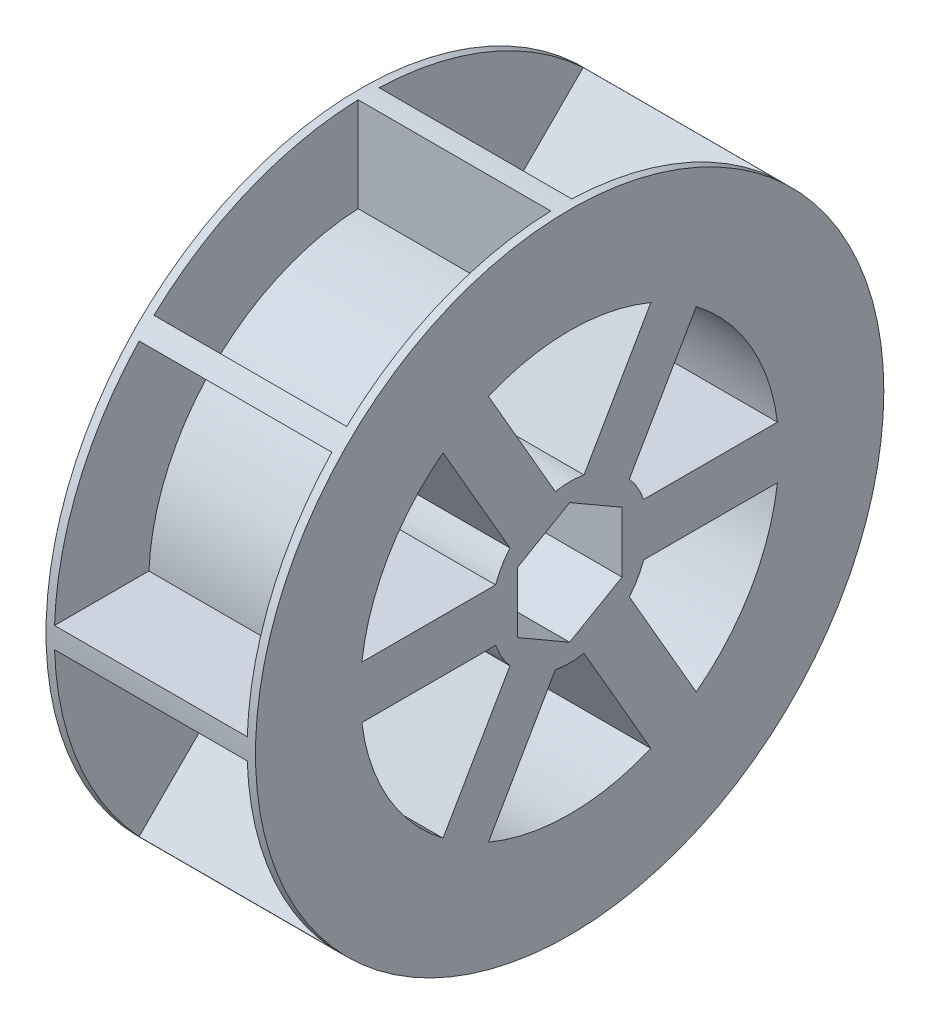
SolidWorks part; units mm, degrees
material "1060 Alloy"
ref_plane "Front Plane" through (0, 0, 0) normal (1, 0, 0) x (0, 1, 0)
ref_plane "Top Plane" through (0, 0, 0) normal (0, 0, 1) x (0, 1, 0)
ref_plane "Right Plane" through (0, 0, 0) normal (0, 1, 0) x (-1, 0, 0)
sketch "Sketch2" plane through (0, 0, 0) normal (1, 0, 0) x (0, 1, 0)
  line L0 (0, -1000) -> (0, -25) construction
  line L1 (14.4338, -25) -> (28.8675, 0)
  line L2 (28.8675, 0) -> (14.4338, 25)
  line L3 (14.4338, 25) -> (-14.4338, 25)
  line L4 (-14.4338, 25) -> (-28.8675, 0)
  line L5 (-28.8675, 0) -> (-14.4338, -25)
  line L6 (-14.4338, -25) -> (14.4338, -25)
  line L7 (-12.5, 25) -> (12.5, 25)
  line L8 (-12.5, 35.3553) -> (-12.5, 100)
  line L9 (-12.5, 100) -> (12.5, 100)
  line L10 (12.5, 35.3553) -> (12.5, 100)
  line L11 (24.3686, 28.503) -> (80.3525, 60.8253)
  line L12 (15.4006, 23.3253) -> (27.9006, 1.6747)
  line L13 (36.8686, 6.8524) -> (92.8525, 39.1747)
  line L14 (80.3525, 60.8253) -> (92.8525, 39.1747)
  line L15 (36.8686, -6.8524) -> (92.8525, -39.1747)
  line L16 (27.9006, -1.6747) -> (15.4006, -23.3253)
  line L17 (24.3686, -28.503) -> (80.3525, -60.8253)
  line L18 (92.8525, -39.1747) -> (80.3525, -60.8253)
  line L19 (12.5, -35.3553) -> (12.5, -100)
  line L20 (12.5, -25) -> (-12.5, -25)
  line L21 (-12.5, -35.3553) -> (-12.5, -100)
  line L22 (12.5, -100) -> (-12.5, -100)
  line L23 (-24.3686, -28.503) -> (-80.3525, -60.8253)
  line L24 (-15.4006, -23.3253) -> (-27.9006, -1.6747)
  line L25 (-36.8686, -6.8524) -> (-92.8525, -39.1747)
  line L26 (-80.3525, -60.8253) -> (-92.8525, -39.1747)
  line L27 (-36.8686, 6.8524) -> (-92.8525, 39.1747)
  line L28 (-27.9006, 1.6747) -> (-15.4006, 23.3253)
  line L29 (-24.3686, 28.503) -> (-80.3525, 60.8253)
  line L30 (-92.8525, 39.1747) -> (-80.3525, 60.8253)
  line L31 (-866.0254, -500) -> (-21.6506, -12.5) construction
  line L32 (0, 25) -> (0, 49000) construction
  line L33 (21.6506, 12.5) -> (42435.2448, 24500) construction
  line L34 (0, -25) -> (0, 25) construction
  line L35 (-21.6506, -12.5) -> (21.6506, 12.5) construction
  circle A0 centre (0, 0) radius 25 construction
  arc A1 (-36.8686, 6.8524) -> (-36.8686, -6.8524) centre (0, 0) ccw
  arc A2 (-12.5, 35.3553) -> (-24.3686, 28.503) centre (0, 0) ccw
  arc A3 (24.3686, 28.503) -> (12.5, 35.3553) centre (0, 0) ccw
  arc A4 (36.8686, -6.8524) -> (36.8686, 6.8524) centre (0, 0) ccw
  arc A5 (12.5, -35.3553) -> (24.3686, -28.503) centre (0, 0) ccw
  arc A6 (-24.3686, -28.503) -> (-12.5, -35.3553) centre (0, 0) ccw
  point P1 (0, 0)
  point P14 (-239.3702, 125.5377)
  point P17 (0, 100)
  point P40 (0, 0)
  point P41 (-242.8812, 98.9859)
  point P45 (0, 0)
  point P49 (0, 0)
  dimension "D1" = 50
  dimension "D2" = 75
  dimension "D3" = 100
  dimension "D4" = 25
  dimension "D6" = 100
  dimension "D5" = 6
extrude "Boss-Extrude1" add sketch "Sketch2" along normal mid plane 100 contours L23 A6 L21 L22 L19 A5 L17 L18 L15 A4 L13 L14 L11 A3 L10 L9 L8 A2 L29 L30 L27 A1 L25 L26 L6 L5 L4 L3 L2 L1
sketch "Sketch4" plane through (50, 0, 0) normal (1, 0, 0) x (0, 1, 0)
  line L0 (0, -1000) -> (0, 49000) construction
  line L1 (-1000, 0) -> (49000, 0) construction
  circle A2 centre (0, 0) radius 100
  circle A3 centre (0, 0) radius 150
  dimension "D1" = 200
  dimension "D2" = 300
extrude "Boss-Extrude3" add sketch "Sketch4" against normal up to surface (100 mm away) contours A3 A2 up to face at (-50, 0, 0)
sketch "Sketch5" plane through (50, 0, 0) normal (1, 0, 0) x (0, 1, 0)
  line L0 (0, -1000) -> (0, 49000) construction
  line L1 (102.5305, 109.6016) -> (70.6265, 77.6975)
  line L2 (-5, 150) -> (5, 150)
  line L3 (-5, 150) -> (-5, 104.8809)
  line L4 (-5, 104.8809) -> (5, 104.8809)
  line L5 (5, 150) -> (5, 104.8809)
  line L6 (102.5305, 109.6016) -> (109.6016, 102.5305)
  line L7 (109.6016, 102.5305) -> (77.6975, 70.6265)
  line L8 (70.6265, 77.6975) -> (77.6975, 70.6265)
  line L9 (150, 5) -> (104.8809, 5)
  line L10 (150, 5) -> (150, -5)
  line L11 (150, -5) -> (104.8809, -5)
  line L12 (104.8809, 5) -> (104.8809, -5)
  line L13 (109.6016, -102.5305) -> (77.6975, -70.6265)
  line L14 (109.6016, -102.5305) -> (102.5305, -109.6016)
  line L15 (102.5305, -109.6016) -> (70.6265, -77.6975)
  line L16 (77.6975, -70.6265) -> (70.6265, -77.6975)
  line L17 (5, -150) -> (5, -104.8809)
  line L18 (5, -150) -> (-5, -150)
  line L19 (-5, -150) -> (-5, -104.8809)
  line L20 (5, -104.8809) -> (-5, -104.8809)
  line L21 (-102.5305, -109.6016) -> (-70.6265, -77.6975)
  line L22 (-102.5305, -109.6016) -> (-109.6016, -102.5305)
  line L23 (-109.6016, -102.5305) -> (-77.6975, -70.6265)
  line L24 (-70.6265, -77.6975) -> (-77.6975, -70.6265)
  line L25 (-150, -5) -> (-104.8809, -5)
  line L26 (-150, -5) -> (-150, 5)
  line L27 (-150, 5) -> (-104.8809, 5)
  line L28 (-104.8809, -5) -> (-104.8809, 5)
  line L29 (-109.6016, 102.5305) -> (-77.6975, 70.6265)
  line L30 (-109.6016, 102.5305) -> (-102.5305, 109.6016)
  line L31 (-102.5305, 109.6016) -> (-70.6265, 77.6975)
  line L32 (-77.6975, 70.6265) -> (-70.6265, 77.6975)
  circle A0 centre (0, 0) radius 105
  circle A1 centre (0, 0) radius 150 construction
  circle A2 centre (0, 0) radius 150
  point P11 (0, 0)
  point P42 (0, 0)
  circle M42 centre (0, 0) radius 150
  dimension "D1" = 210
  dimension "D2" = 10
  dimension "D3" = 8
extrude "Cut-Extrude1" cut sketch "Sketch5" against normal blind 120 contours A0 L3 L31 M42 | A0 L1 L5 M42 | A0 L9 L7 M42 | A0 L13 L11 M42 | A0 L17 L15 M42 | A0 L21 L19 M42 | A0 L25 L23 M42 | A0 L29 L27 M42
sketch "Sketch7" plane through (50, 0, 0) normal (1, 0, 0) x (0, 1, 0)
  circle A0 centre (0, 0) radius 105
  arc A1 (104.8809, 5) -> (77.6975, 70.6265) centre (0, 0) ccw construction
  circle A2 centre (0, 0) radius 150
extrude "Boss-Extrude6" add sketch "Sketch7" against normal blind 4
mirror "Mirror2" about plane through (0, 0, 0) normal (1, 0, 0) of "Boss-Extrude6"
sketch "Sketch6" [suppressed] plane through (60, 0, 0) normal (1, 0, 0) x (0, 1, 0)
  line L0 (-14.4338, 25) -> (-28.8675, 0) construction
  line L1 (-28.8675, 0) -> (-14.4338, -25) construction
  line L2 (-14.4338, -25) -> (14.4338, -25) construction
  line L3 (14.4338, -25) -> (28.8675, 0) construction
  line L4 (28.8675, 0) -> (14.4338, 25) construction
  line L5 (14.4338, 25) -> (-14.4338, 25) construction
  line L6 (-14.4338, 25) -> (-28.8675, 0)
  line L7 (-28.8675, 0) -> (-14.4338, -25)
  line L8 (-14.4338, -25) -> (14.4338, -25)
  line L9 (14.4338, -25) -> (28.8675, 0)
  line L10 (28.8675, 0) -> (14.4338, 25)
  line L11 (14.4338, 25) -> (-14.4338, 25)
  circle A0 centre (0, 0) radius 150
extrude "Boss-Extrude4" [suppressed] add sketch "Sketch6" along normal blind 4
mirror "Mirror1" [suppressed] about plane through (0, 0, 0) normal (1, 0, 0)
